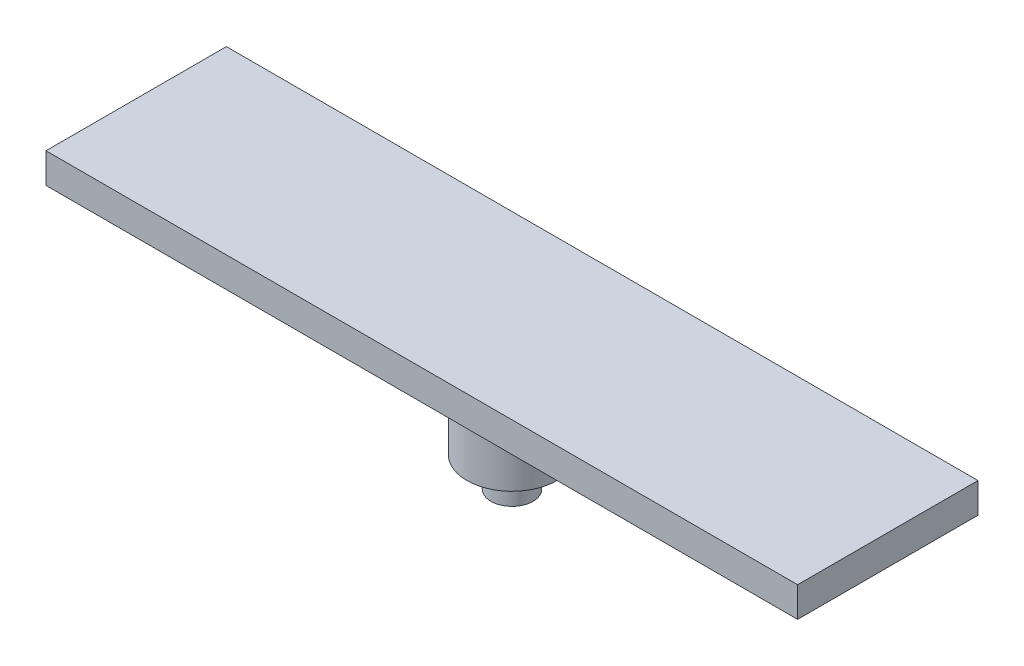
SolidWorks part; units mm, degrees
ref_plane "Front Plane" through (0, 0, 0) normal (0, 0, 1) x (1, 0, 0)
ref_plane "Top Plane" through (0, 0, 0) normal (0, 1, 0) x (1, 0, 0)
ref_plane "Right Plane" through (0, 0, 0) normal (1, 0, 0) x (0, 0, -1)
sketch "Sketch1" plane through (0, 0, 0) normal (0, 1, 0) x (1, 0, 0)
  circle A0 centre (0, 0) radius 7.5
  dimension "D1" = 15
extrude "Boss-Extrude1" add sketch "Sketch1" along normal blind 15
sketch "Sketch2" plane through (0, 15, 0) normal (0, 1, 0) x (1, 0, 0)
  line L1 (-62.5, -15) -> (62.5, -15)
  line L2 (-62.5, -15) -> (-62.5, 15)
  line L3 (-62.5, 15) -> (62.5, 15)
  line L4 (62.5, -15) -> (62.5, 15)
  line L5 (-62.5, -15) -> (62.5, 15) construction
  line L6 (-62.5, 15) -> (62.5, -15) construction
  point P0 (0, 0)
  dimension "D1" = 30
  dimension "D2" = 125
extrude "Boss-Extrude2" add sketch "Sketch2" along normal blind 5
sketch "Sketch3" plane through (0, 0, 0) normal (0, -1, 0) x (1, 0, 0)
  circle A0 centre (0, 0) radius 3.5
  dimension "D1" = 7
extrude "Boss-Extrude3" add sketch "Sketch3" along normal blind 5
